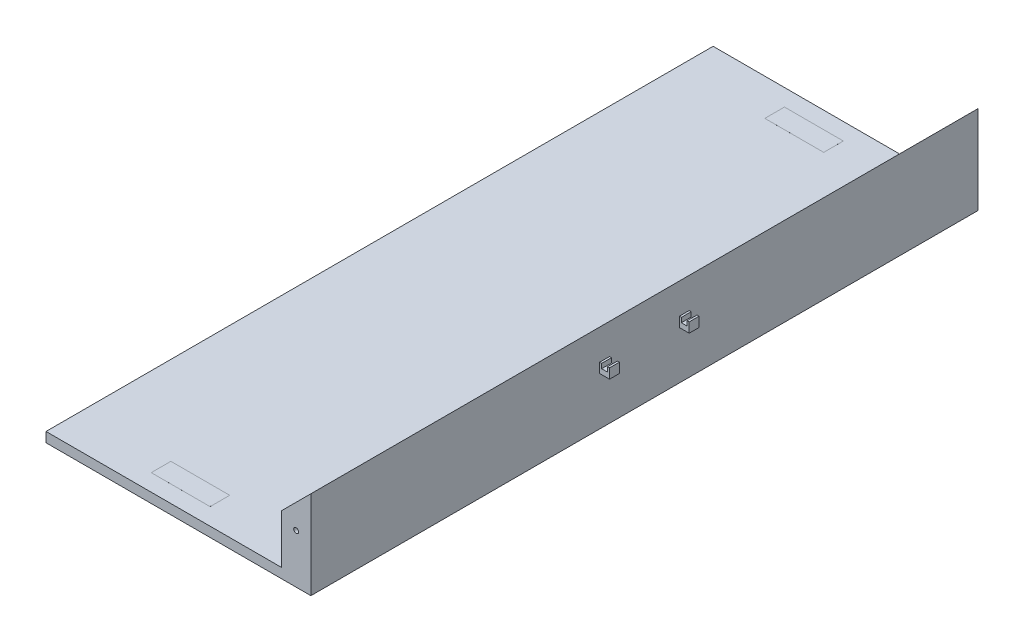
SolidWorks part; units mm, degrees
ref_plane "Front Plane" through (0, 0, 0) normal (0, 0, 1) x (1, 0, 0)
ref_plane "Top Plane" through (0, 0, 0) normal (0, 1, 0) x (1, 0, 0)
ref_plane "Right Plane" through (0, 0, 0) normal (1, 0, 0) x (0, 0, -1)
sketch "Sketch1" plane through (0, 0, 0) normal (0, 0, 1) x (1, 0, 0)
  line L0 (0, 0) -> (38.1, 0)
  line L1 (0, 0) -> (0, 76.2)
  line L2 (0, 76.2) -> (19.7161, 95.9161)
  line L3 (38.1, 0) -> (38.1, 114.3)
  line L4 (19.7161, 95.9161) -> (38.1, 114.3)
  dimension "D1" = 38.1
  dimension "D2" = 76.2
  dimension "D3" = 135
extrude "Boss-Extrude1" add sketch "Sketch1" along normal blind 863.6
sketch "Sketch2" plane through (0, 0, 0) normal (0, 0, -1) x (-1, 0, 0)
  line L0 (0, 76.2) -> (0, 0) construction
  line L1 (0, 12.7) -> (304.8, 12.7)
  line L2 (0, 12.7) -> (0, 0)
  line L3 (0, 0) -> (304.8, 0)
  line L4 (304.8, 12.7) -> (304.8, 0)
  point P6 (0, 0)
  dimension "D1" = 304.8
  dimension "D2" = 12.7
sketch "Sketch3" plane through (0, 0, 863.6) normal (0, 0, 1) x (1, 0, 0)
  line L0 (0, 76.2) -> (38.1, 76.2) construction
  line L1 (38.1, 0) -> (38.1, 114.3) construction
  circle A0 centre (19.05, 63.5) radius 3.175
  dimension "D1" = 12.7
extrude "Cut-Extrude1" cut sketch "Sketch3" against normal blind 863.6
extrude "Boss-Extrude5" add sketch "Sketch2" against normal blind 863.6
sketch "Sketch5" plane through (0, 12.7, 0) normal (0, 1, 0) x (1, 0, 0)
  line L0 (-304.8, -431.8) -> (0, -431.8) construction
  line L1 (-304.8, -863.6) -> (-304.8, 0) construction
  line L2 (0, -863.6) -> (0, 0) construction
  line L3 (-152.4, -431.8) -> (-152.4, 0) construction
  line L4 (-190.5, -21.9368) -> (-114.3, -21.9368)
  line L5 (-190.5, -21.9368) -> (-190.5, -47.3368)
  line L6 (-190.5, -47.3368) -> (-114.3, -47.3368)
  line L7 (-114.3, -21.9368) -> (-114.3, -47.3368)
  line L8 (-190.5, -21.9368) -> (-114.3, -47.3368) construction
  line L9 (-190.5, -47.3368) -> (-114.3, -21.9368) construction
  line L10 (-304.8, 0) -> (0, 0) construction
  line L11 (-190.5, -841.6632) -> (-190.5, -816.2632)
  line L12 (-190.5, -816.2632) -> (-114.3, -816.2632)
  line L13 (-114.3, -841.6632) -> (-114.3, -816.2632)
  line L14 (-190.5, -841.6632) -> (-114.3, -841.6632)
  point P6 (-152.4, -34.6368)
  point P11 (-152.4, -34.6368)
  dimension "D1" = 76.2
  dimension "D2" = 25.4
extrude "Boss-Extrude6" add sketch "Sketch5" along normal blind 0.0127
sketch "Sketch6" plane through (38.1, 0, 0) normal (1, 0, 0) x (0, 0, -1)
  line L0 (-431.8, 114.3) -> (-431.8, 0) construction
  line L1 (-863.6, 114.3) -> (0, 114.3) construction
  line L2 (-863.6, 0) -> (0, 0) construction
  line L3 (-373.8861, 62.1343) -> (-386.5861, 62.1343)
  line L4 (-489.7139, 74.8343) -> (-477.0139, 74.8343)
  line L5 (-489.7139, 74.8343) -> (-489.7139, 62.1343)
  line L6 (-489.7139, 62.1343) -> (-477.0139, 62.1343)
  line L7 (-477.0139, 74.8343) -> (-477.0139, 62.1343)
  line L8 (-489.7139, 74.8343) -> (-477.0139, 62.1343) construction
  line L9 (-489.7139, 62.1343) -> (-477.0139, 74.8343) construction
  line L10 (-386.5861, 74.8343) -> (-386.5861, 62.1343)
  line L11 (-373.8861, 74.8343) -> (-386.5861, 74.8343)
  line L12 (-373.8861, 74.8343) -> (-373.8861, 62.1343)
  point P6 (-483.3639, 68.4843)
  dimension "D1" = 12.7
  dimension "D2" = 12.7
extrude "Boss-Extrude8" add sketch "Sketch6" along normal blind 12.7
sketch "Sketch7" plane through (0, 0, 489.7139) normal (0, 0, 1) x (1, 0, 0)
  line L1 (50.8, 74.8343) -> (38.1, 74.8343) construction
  line L2 (44.45, 68.8121) -> (48.2225, 68.8121)
  line L3 (48.2225, 68.8121) -> (48.2225, 74.8343)
  line L4 (48.2225, 74.8343) -> (40.6685, 74.8343)
  line L5 (40.6685, 74.8343) -> (40.6685, 68.8121)
  line L6 (40.6685, 68.8121) -> (44.45, 68.8121)
extrude "Cut-Extrude2" cut sketch "Sketch7" against normal blind 137.668
